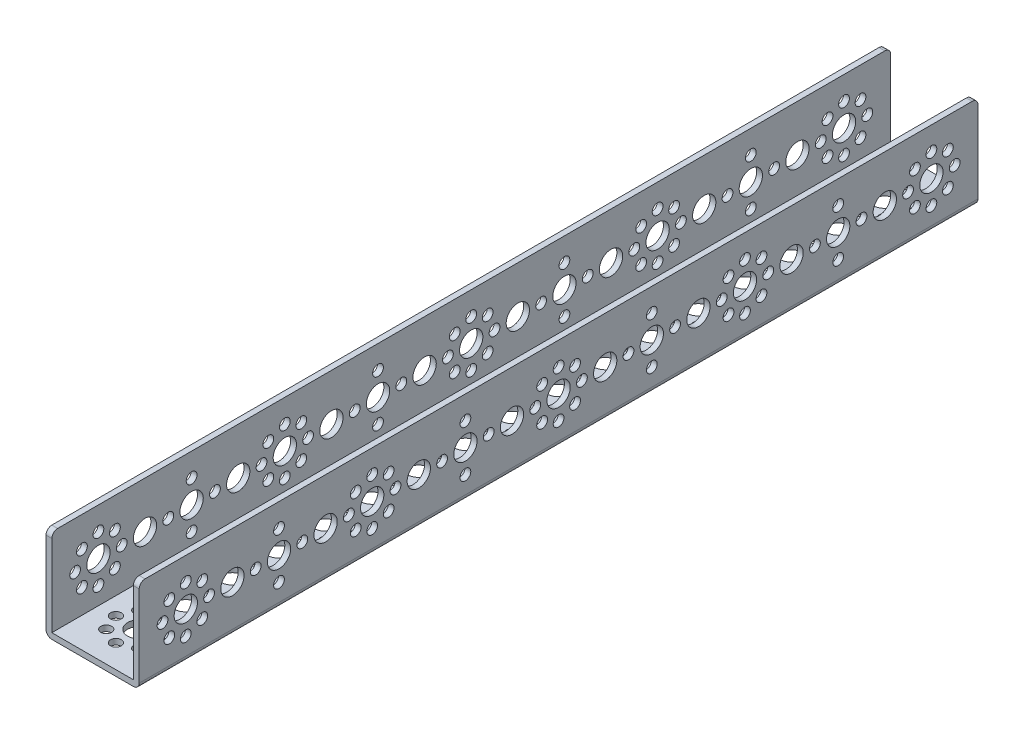
SolidWorks part; units mm, degrees
other "Defeature"
material "5052 Alloy"
ref_plane "Front Plane" through (0, 0, 0) normal (0, 0, 1) x (1, 0, 0)
ref_plane "Top Plane" through (0, 0, 0) normal (0, 1, 0) x (1, 0, 0)
ref_plane "Right Plane" through (0, 0, 0) normal (1, 0, 0) x (0, 0, -1)
sketch "Sketch1" plane through (0, 0, 0) normal (0, 0, 1) x (1, 0, 0)
  line L0 (-14, 0) -> (14, 0)
  line L1 (16, 2) -> (16, 32)
  line L2 (16, 32) -> (14, 32)
  line L3 (14, 32) -> (14, 2)
  line L4 (14, 2) -> (-14, 2)
  line L5 (-14, 2) -> (-14, 32)
  line L6 (-14, 32) -> (-16, 32)
  line L7 (-16, 32) -> (-16, 2)
  arc A0 (-16, 2) -> (-14, 0) centre (-14, 2) ccw
  arc A1 (16, 2) -> (14, 0) centre (14, 2) cw
  point P11 (0, 0)
  point P14 (16, 0)
  dimension "D6" = 2
  dimension "D1" = 32
  dimension "D2" = 2
  dimension "D3" = 2
  dimension "D4" = 32
  dimension "D5" = 2
extrude "Boss-Extrude1" add sketch "Sketch1" against normal mid plane 288
sketch "Sketch2" plane through (16, 0, 0) normal (1, 0, 0) x (0, 0, -1)
  line L1 (144, 32) -> (-144, 32) construction
  line L2 (144, 0) -> (-144, 0) construction
  point P5 (0, 32)
  circle B0 centre (-96, 16) radius 4
  circle B1 centre (-88, 16) radius 1.85
  circle B2 centre (-104, 16) radius 1.85
  circle B3 centre (-96, 8) radius 1.85
  circle B4 centre (-96, 24) radius 1.85
  circle B5 centre (-112, 16) radius 4
  circle B6 centre (-80, 16) radius 4
  circle B7 centre (-48, 16) radius 4
  circle B8 centre (-16, 16) radius 4
  circle B9 centre (-122.3431, 21.6569) radius 1.85
  circle B10 centre (-128, 24) radius 1.85
  circle B11 centre (-133.6569, 21.6569) radius 1.85
  circle B12 centre (-128, 16) radius 4
  circle B13 centre (-120, 16) radius 1.85
  circle B14 centre (-136, 16) radius 1.85
  circle B15 centre (-128, 8) radius 1.85
  circle B16 centre (-122.3431, 10.3431) radius 1.85
  circle B17 centre (-133.6569, 10.3431) radius 1.85
  circle B18 centre (-32, 16) radius 4
  circle B19 centre (-24, 16) radius 1.85
  circle B20 centre (-40, 16) radius 1.85
  circle B21 centre (-32, 8) radius 1.85
  circle B22 centre (-32, 24) radius 1.85
  circle B23 centre (-64, 16) radius 4
  circle B24 centre (-56, 16) radius 1.85
  circle B25 centre (-72, 16) radius 1.85
  circle B26 centre (-64, 8) radius 1.85
  circle B27 centre (-64, 24) radius 1.85
  circle B28 centre (-69.6569, 21.6569) radius 1.85
  circle B29 centre (-58.3431, 21.6569) radius 1.85
  circle B30 centre (-58.3431, 10.3431) radius 1.85
  circle B31 centre (-69.6569, 10.3431) radius 1.85
  circle B32 centre (-96, 16) radius 8 construction
  line B33 (-133.6569, 21.6569) -> (-122.3431, 10.3431) construction
  line B34 (-133.6569, 10.3431) -> (-122.3431, 21.6569) construction
  line B35 (-128, 16) -> (-128, 8) construction
  circle B36 centre (-128, 16) radius 8 construction
  circle B37 centre (8, 16) radius 1.85
  circle B38 centre (0, 8) radius 1.85
  circle B39 centre (0, 16) radius 4
  circle B40 centre (0, 24) radius 1.85
  circle B41 centre (-5.6569, 21.6569) radius 1.85
  circle B42 centre (-5.6569, 10.3431) radius 1.85
  circle B43 centre (-8, 16) radius 1.85
  circle B44 centre (5.6569, 21.6569) radius 1.85
  circle B45 centre (5.6569, 10.3431) radius 1.85
  dimension "D1" = 16
sketch_block_instance "Block6-1"
sketch_block "Block6" parameters "D8"=8, "D1"=16, "D2"=16, "D3"=16, "D4"=16, "D5"=16, "D6"=16, "D7"=16, "D9"=21.9346
sketch_block_instance "Block5-1"
sketch_block "Block5" parameters "D1"=16, "D2"=3.7, "D3"=8
sketch_block_instance "Block2-4"
sketch_block "Block2" parameters "D1"=3.7, "D2"=16, "D3"=8, "D4"=16
sketch_block_instance "Block5-2"
sketch_block_instance "Block2-5"
sketch_block_instance "Block2-13"
extrude "Cut-Extrude1" cut sketch "Sketch2" against normal through all
sketch "Sketch5" plane through (0, 0, 0) normal (0, -1, 0) x (1, 0, 0)
  line L0 (0, 0) -> (0, 32) construction
  line L1 (0, 32) -> (0, 64) construction
  line L2 (0, 64) -> (0, 96) construction
  line L3 (0, 96) -> (0, 128) construction
  line L4 (-14, -144) -> (-14, 144) construction
  circle A0 centre (0, 112) radius 4
  circle A1 centre (0, 80) radius 4
  circle A2 centre (0, 48) radius 4
  circle A3 centre (0, 16) radius 4
  circle B0 centre (0, 96) radius 4
  circle B1 centre (0, 88) radius 1.85
  circle B2 centre (0, 104) radius 1.85
  circle B3 centre (-8, 96) radius 1.85
  circle B4 centre (8, 96) radius 1.85
  circle B5 centre (0, 120) radius 1.85
  circle B6 centre (-8, 128) radius 1.85
  circle B7 centre (0, 128) radius 4
  circle B8 centre (8, 128) radius 1.85
  circle B9 centre (5.6569, 133.6569) radius 1.85
  circle B10 centre (-5.6569, 133.6569) radius 1.85
  circle B11 centre (0, 136) radius 1.85
  circle B12 centre (5.6569, 122.3431) radius 1.85
  circle B13 centre (-5.6569, 122.3431) radius 1.85
  circle B14 centre (0, 56) radius 1.85
  circle B15 centre (-8, 64) radius 1.85
  circle B16 centre (0, 64) radius 4
  circle B17 centre (8, 64) radius 1.85
  circle B18 centre (5.6569, 69.6569) radius 1.85
  circle B19 centre (-5.6569, 69.6569) radius 1.85
  circle B20 centre (0, 72) radius 1.85
  circle B21 centre (5.6569, 58.3431) radius 1.85
  circle B22 centre (-5.6569, 58.3431) radius 1.85
  circle B23 centre (-8, 0) radius 1.85
  circle B24 centre (0, 8) radius 1.85
  circle B25 centre (0, 0) radius 4
  circle B26 centre (0, -8) radius 1.85
  circle B27 centre (5.6569, -5.6569) radius 1.85
  circle B28 centre (5.6569, 5.6569) radius 1.85
  circle B29 centre (8, 0) radius 1.85
  circle B30 centre (-5.6569, -5.6569) radius 1.85
  circle B31 centre (-5.6569, 5.6569) radius 1.85
  circle B32 centre (0, 32) radius 4
  circle B33 centre (8, 32) radius 1.85
  circle B34 centre (-8, 32) radius 1.85
  circle B35 centre (0, 24) radius 1.85
  circle B36 centre (0, 40) radius 1.85
  dimension "D1" = 8
  dimension "D2" = 32
sketch_block_instance "Block5-5"
sketch_block_instance "Block2-17"
sketch_block_instance "Block2-18"
sketch_block_instance "Block2-19"
sketch_block_instance "Block5-7"
extrude "Cut-Extrude2" cut sketch "Sketch5" against normal up to surface (2 mm away) up to face at (0, 2, 0)
fillet "Fillet1" radius 2 4 edges at (15, 32, 144) (-15, 32, -144) (15, 32, -144) (-15, 32, 144)
mirror "Mirror1" about plane through (0, 0, 0) normal (0, 0, 1) of "Cut-Extrude2", "Cut-Extrude1"
